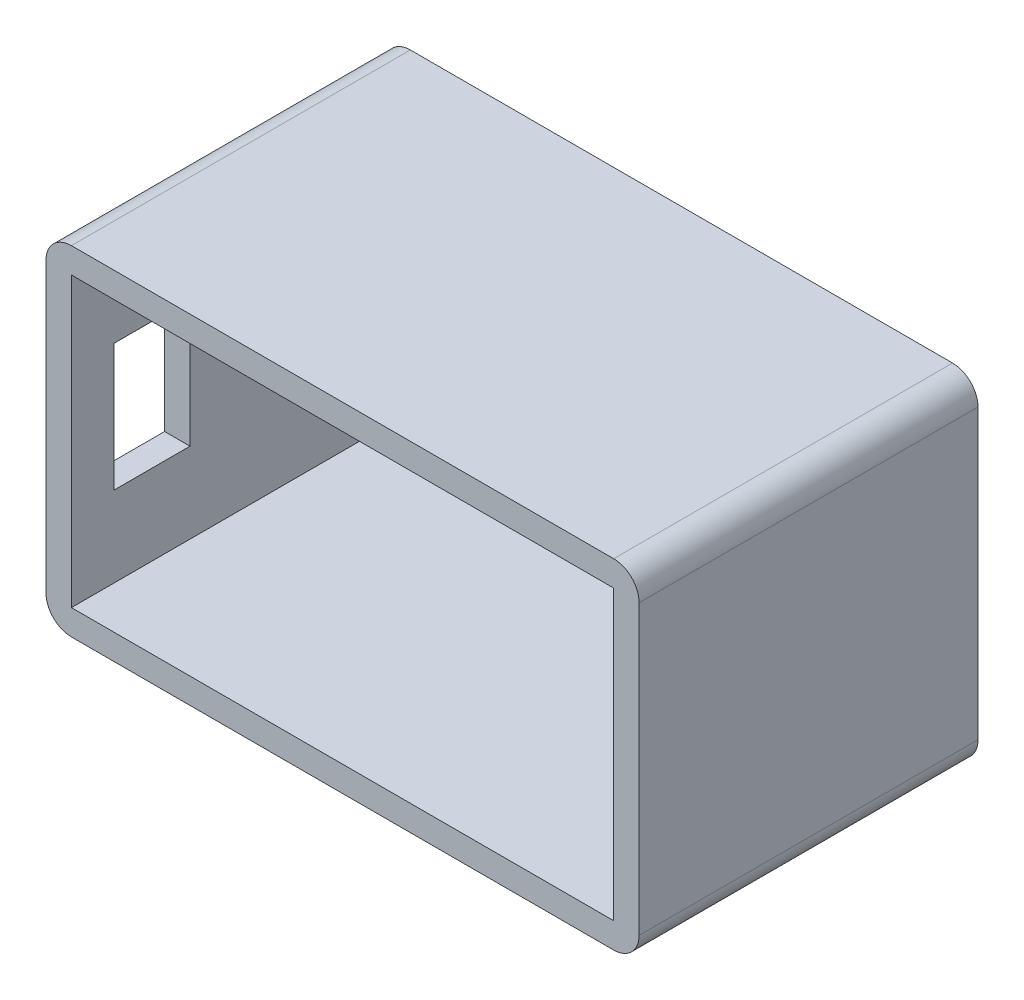
SolidWorks part; units mm, degrees
ref_plane "Front Plane" through (0, 0, 0) normal (0, 0, 1) x (1, 0, 0)
ref_plane "Top Plane" through (0, 0, 0) normal (0, 1, 0) x (1, 0, 0)
ref_plane "Right Plane" through (0, 0, 0) normal (1, 0, 0) x (0, 0, -1)
sketch "Sketch1" plane through (0, 0, 0) normal (0, 0, 1) x (1, 0, 0)
  line L1 (-35, -20) -> (35, -20)
  line L2 (-35, -20) -> (-35, 20)
  line L3 (-35, 20) -> (35, 20)
  line L4 (35, -20) -> (35, 20)
  line L5 (-35, -20) -> (35, 20) construction
  line L6 (-35, 20) -> (35, -20) construction
  point P0 (0, 0)
  dimension "D1" = 70
  dimension "D2" = 40
extrude "Boss-Extrude2" add sketch "Sketch1" along normal blind 40
shell "Shell2" thickness 3
sketch "Sketch2" plane through (0, 0, 0) normal (0, 0, -1) x (-1, 0, 0)
  circle A0 centre (0, 0) radius 3.5
  dimension "D1" = 7
extrude "Cut-Extrude1" cut sketch "Sketch2" against normal blind 40
sketch "Sketch5" plane through (-35, 0, 0) normal (-1, 0, 0) x (0, 0, 1)
  line L0 (0, 0) -> (40, 0) construction
  line L1 (40, 20) -> (40, -20) construction
  line L3 (35, -7.5) -> (26, -7.5)
  line L4 (35, -7.5) -> (35, 7.5)
  line L5 (35, 7.5) -> (26, 7.5)
  line L6 (26, -7.5) -> (26, 7.5)
  line L7 (35, -7.5) -> (26, 7.5) construction
  line L8 (35, 7.5) -> (26, -7.5) construction
  point P5 (30.5, 0)
  dimension "D1" = 5
  dimension "D2" = 15
  dimension "D3" = 9
extrude "Cut-Extrude2" cut sketch "Sketch5" against normal blind 40
fillet "Fillet1" radius 3 4 edges at (35, -20, 20) (35, 20, 20) (-35, 20, 20) (-35, -20, 20)
